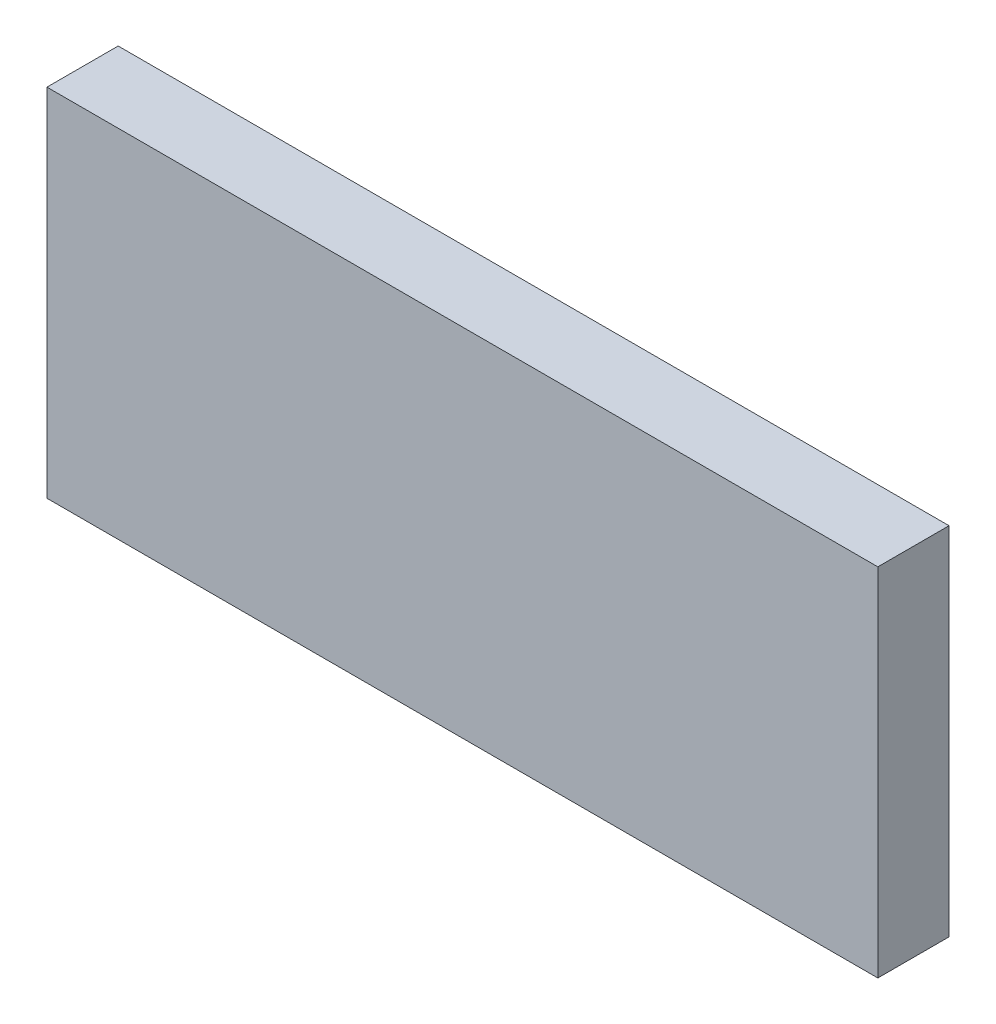
SolidWorks part; units mm, degrees
material "Pine"
ref_plane "Piano frontale" through (0, 0, 0) normal (0, 0, 1) x (1, 0, 0)
ref_plane "Piano superiore" through (0, 0, 0) normal (0, 1, 0) x (1, 0, 0)
ref_plane "Piano destro" through (0, 0, 0) normal (1, 0, 0) x (0, 0, -1)
sketch "Sketch1" plane through (0, 0, 0) normal (0, 0, 1) x (1, 0, 0)
  line L1 (0, 0) -> (17.5, 0)
  line L2 (0, 0) -> (0, 7.5)
  line L3 (0, 7.5) -> (17.5, 7.5)
  line L4 (17.5, 0) -> (17.5, 7.5)
  dimension "D1" = 17.5
  dimension "D2" = 7.5
extrude "Boss-Extrude1" add sketch "Sketch1" along normal blind 1.5
scale "Scale1" scale about origin uniform scaling yes scale factor 10
